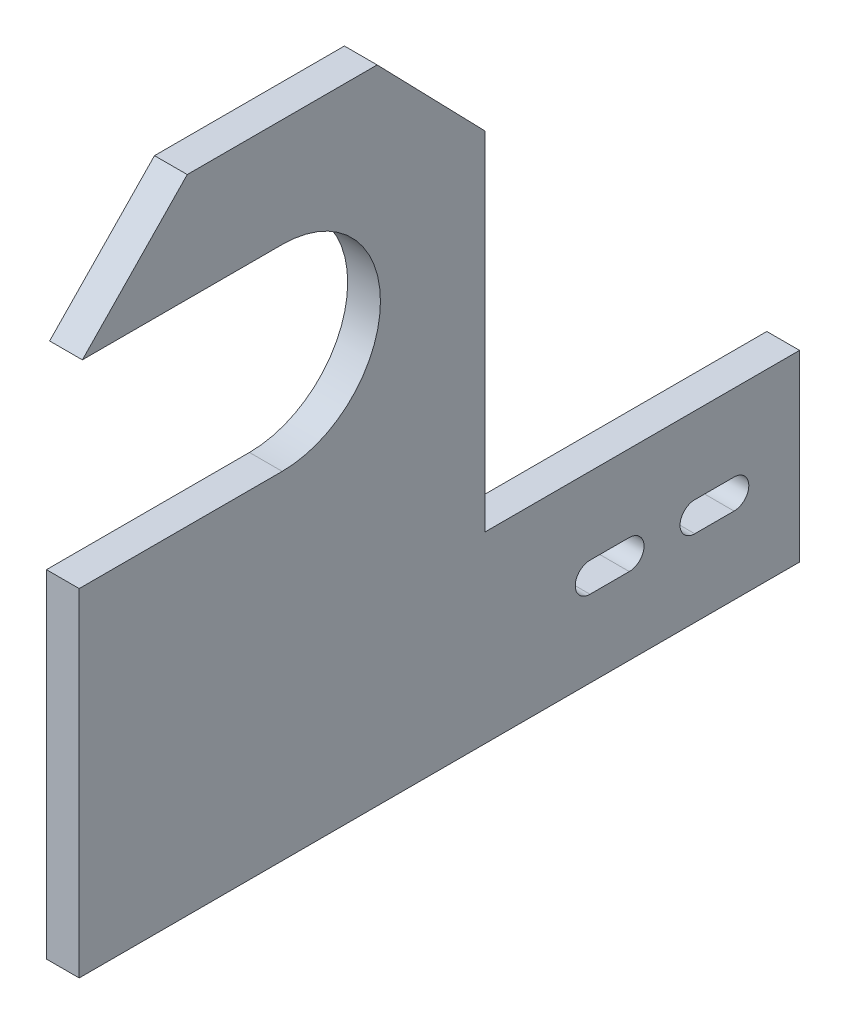
SolidWorks part; units mm, degrees
ref_plane "Plano frontal" through (0, 0, 0) normal (0, 0, 1) x (1, 0, 0)
ref_plane "Plano superior" through (0, 0, 0) normal (0, 1, 0) x (1, 0, 0)
ref_plane "Plano direito" through (0, 0, 0) normal (1, 0, 0) x (0, 0, -1)
sketch "Esboço2" plane through (0, 0, 0) normal (1, 0, 0) x (0, 0, -1)
  line L0 (0.4853, 49.5) -> (16.5, 66)
  line L1 (0, 0) -> (62, 0)
  line L2 (0, 0) -> (0, 19.5)
  line L4 (62, 0) -> (62, 49)
  line L5 (16.5, 66) -> (45.5, 66)
  line L6 (45.5, 66) -> (62, 49)
  line L7 (31, 0) -> (31, 66) construction
  line L8 (31, 49.5) -> (0.4853, 49.5)
  line L10 (0, 19.5) -> (31, 19.5)
  arc A0 (31, 19.5) -> (31, 49.5) centre (31, 34.5) ccw
  point P4 (31, 66)
  dimension "D5" = 30
  dimension "D1" = 66
  dimension "D3" = 62
  dimension "D4" = 29
  dimension "D6" = 34.5
extrude "Ressalto-extrusão2" add sketch "Esboço2" against normal blind 5 contours L0 L5 L6 L4 L1 L2 L10 A0 L8
sketch "Esboço3" plane through (0, 0, 0) normal (1, 0, 0) x (0, 0, -1)
  line L0 (62, 0) -> (62, 49) construction
  line L1 (0, 0) -> (62, 0)
  line L2 (0, 0) -> (0, -32)
  line L3 (0, -32) -> (110, -32)
  line L4 (62, 0) -> (62, -4)
  line L7 (62, -4) -> (110, -4)
  line L8 (110, -32) -> (110, -4)
  line L9 (78, -18) -> (84, -18) construction
  line L10 (78, -15.75) -> (84, -15.75)
  line L11 (78, -20.25) -> (84, -20.25)
  line L12 (94, -18) -> (100, -18) construction
  line L13 (94, -15.75) -> (100, -15.75)
  line L14 (94, -20.25) -> (100, -20.25)
  arc A2 (78, -15.75) -> (78, -20.25) centre (78, -18) ccw
  arc A3 (84, -20.25) -> (84, -15.75) centre (84, -18) ccw
  arc A4 (94, -15.75) -> (94, -20.25) centre (94, -18) ccw
  arc A5 (100, -20.25) -> (100, -15.75) centre (100, -18) ccw
  point P13 (81, -18)
  point P20 (97, -18)
  dimension "D4" = 14
  dimension "D6" = 2.25
  dimension "D1" = 32
  dimension "D2" = 110
  dimension "D3" = 28
  dimension "D5" = 6
  dimension "D7" = 10
  dimension "D8" = 10
extrude "Ressalto-extrusão3" add sketch "Esboço3" against normal up to surface (5 mm away) up to face at (-5, 35.4444, -29.2761)
